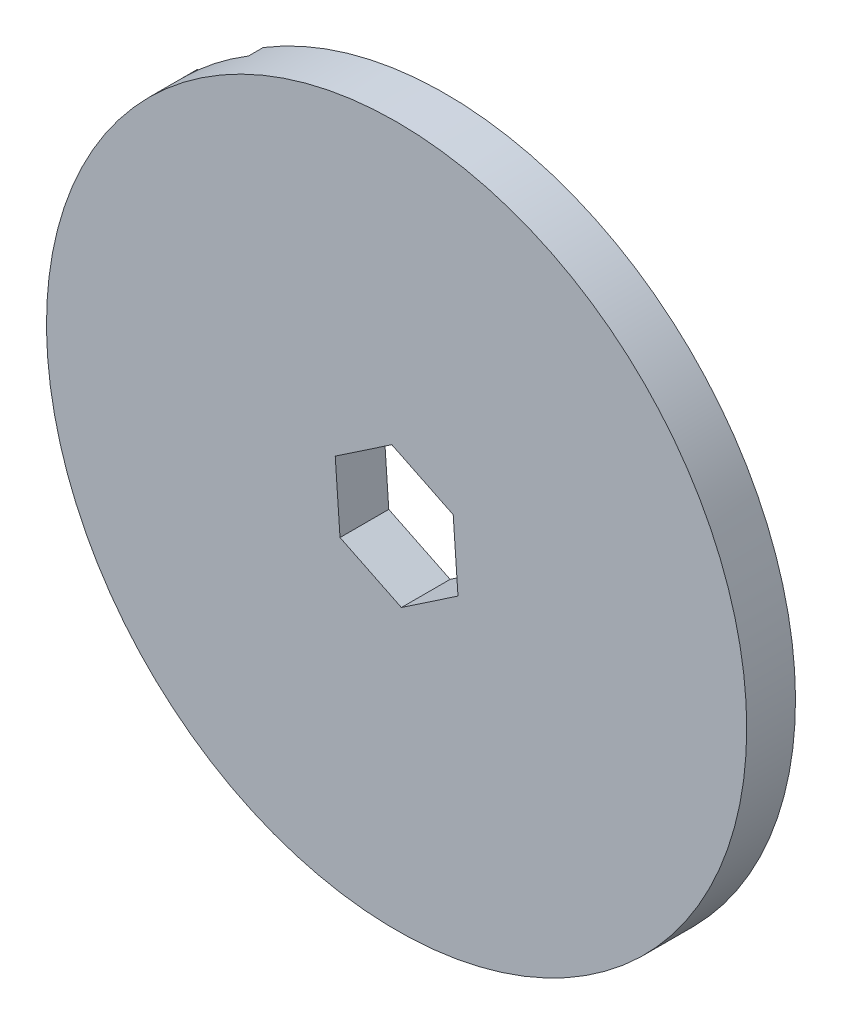
SolidWorks part; units mm, degrees
ref_plane "前视基准面" through (0, 0, 0) normal (0, 0, 1) x (1, 0, 0)
ref_plane "上视基准面" through (0, 0, 0) normal (0, 1, 0) x (1, 0, 0)
ref_plane "右视基准面" through (0, 0, 0) normal (1, 0, 0) x (0, 0, -1)
other "Configuration Table"
sketch "草图1" plane through (0, 0, 0) normal (0, 0, 1) x (1, 0, 0)
  line L1 (6.2927, -3.0663) -> (5.8019, 3.9164)
  line L2 (5.8019, 3.9164) -> (-0.4908, 6.9828)
  line L3 (-0.4908, 6.9828) -> (-6.2927, 3.0663)
  line L4 (-6.2927, 3.0663) -> (-5.8019, -3.9164)
  line L5 (-5.8019, -3.9164) -> (0.4908, -6.9828)
  line L6 (0.4908, -6.9828) -> (6.2927, -3.0663)
  circle A0 centre (0, 0) radius 35.9
  circle A1 centre (0, 0) radius 6.0622 construction
  dimension "D1" = 71.8
  dimension "D2" = 14
extrude "凸台-拉伸1" add sketch "草图1" along normal blind 5
sketch "草图2" plane through (0, 0, 0) normal (0, 0, -1) x (-1, 0, 0)
  line L0 (18.6823, 30.6559) -> (15.2422, 25.8394)
  line L1 (21.4106, 21.014) -> (25.4038, 25.3664)
  arc A0 (18.6823, 30.6559) -> (25.4038, 25.3664) centre (0, 0) cw
  circle A1 centre (0, 0) radius 35.9 construction
  arc A2 (15.2422, 25.8394) -> (21.4106, 21.014) centre (0, 0) cw
  dimension "D2" = 30
  dimension "D1" = 7
extrude "切除-拉伸1" cut sketch "草图2" against normal blind 1.5
pattern_circular "阵列(圆周)1" count 2 over 360 about axis through (0, 0, 0) along (0, 0, 1) of "切除-拉伸1"
